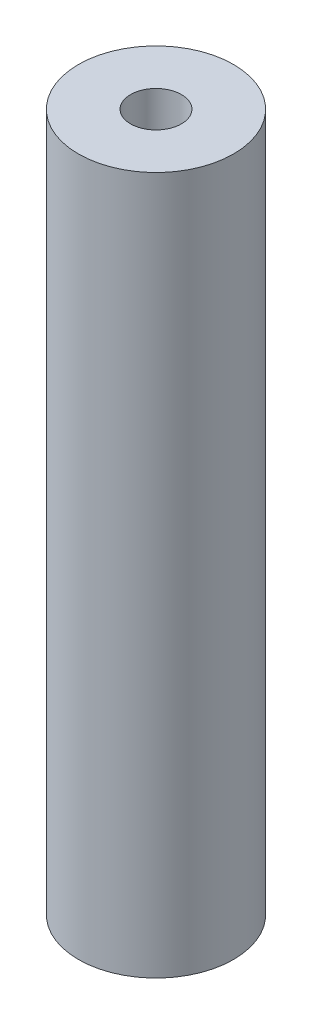
SolidWorks part; units mm, degrees
ref_plane "前视基准面" through (0, 0, 0) normal (0, 0, 1) x (1, 0, 0)
ref_plane "上视基准面" through (0, 0, 0) normal (0, 1, 0) x (1, 0, 0)
ref_plane "右视基准面" through (0, 0, 0) normal (1, 0, 0) x (0, 0, -1)
other "Configuration Table"
sketch "草图1" plane through (0, 0, 0) normal (0, 1, 0) x (1, 0, 0)
  circle A0 centre (0, 0) radius 4.725
  circle A1 centre (0, 0) radius 1.55
  dimension "D1" = 9.45
  dimension "D2" = 3.1
extrude "凸台-拉伸1" add sketch "草图1" along normal blind 42.5
